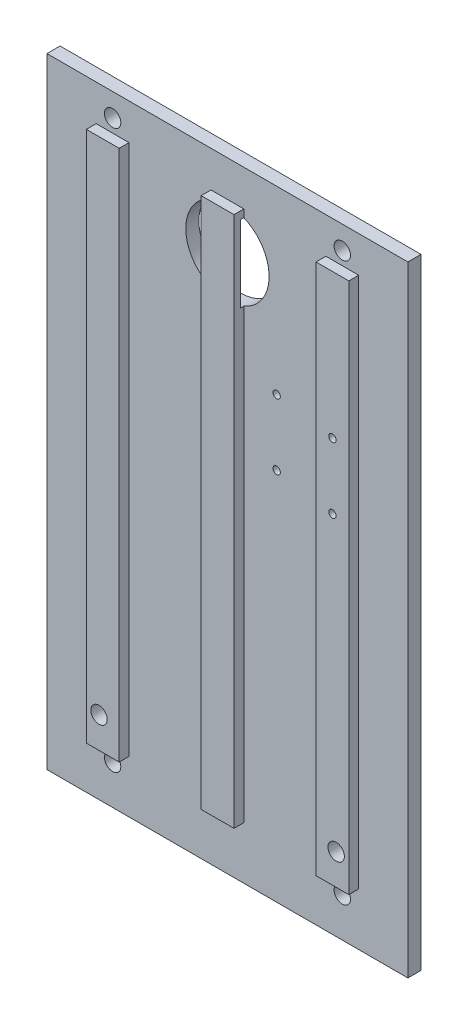
SolidWorks part; units mm, degrees
ref_plane "Front Plane" through (0, 0, 0) normal (0, 0, 1) x (1, 0, 0)
ref_plane "Top Plane" through (0, 0, 0) normal (0, 1, 0) x (1, 0, 0)
ref_plane "Right Plane" through (0, 0, 0) normal (1, 0, 0) x (0, 0, -1)
sketch "Sketch1" plane through (0, 0, 0) normal (0, 0, 1) x (1, 0, 0)
  line L1 (0, 0) -> (110, 0)
  line L2 (0, 0) -> (0, 189)
  line L3 (0, 189) -> (110, 189)
  line L4 (110, 0) -> (110, 189)
extrude "Boss-Extrude1" add sketch "Sketch1" along normal blind 4
sketch "Sketch2" plane through (0, 0, 4) normal (0, 0, 1) x (1, 0, 0)
  line L0 (55, 189) -> (55, 0) construction
  line L1 (110, 189) -> (0, 189) construction
  line L2 (0, 0) -> (110, 0) construction
  line L3 (0, 189) -> (0, 0) construction
  line L4 (110, 0) -> (110, 189) construction
  line L5 (110, 189) -> (0, 189) construction
  circle A1 centre (20, 12) radius 2.5
  circle A2 centre (90, 12) radius 2.5
  circle A3 centre (18.86, 25.4) radius 2.5
  circle A4 centre (91.14, 25.4) radius 2.5
  circle A5 centre (20, 182) radius 2.5
  circle A6 centre (90, 182) radius 2.5
  circle A7 centre (20, 134) radius 1.12 construction
  circle A8 centre (40, 134) radius 1.12 construction
  circle A9 centre (20, 114) radius 1.12 construction
  circle A10 centre (40, 114) radius 1.12 construction
  circle A11 centre (55, 164) radius 12.7
  circle A12 centre (70, 134) radius 1.12
  circle A13 centre (90, 134) radius 1.12
  circle A14 centre (90, 114) radius 1.12
  circle A15 centre (70, 114) radius 1.12
  dimension "D1" = 5
  dimension "D2" = 5
  dimension "D3" = 12
  dimension "D4" = 12
  dimension "D5" = 20
  dimension "D6" = 20
  dimension "D7" = 5
  dimension "D8" = 5
  dimension "D9" = 18.86
  dimension "D10" = 18.86
  dimension "D11" = 25.4
  dimension "D12" = 25.4
  dimension "D13" = 5
  dimension "D14" = 5
  dimension "D15" = 20
  dimension "D16" = 20
  dimension "D17" = 7
  dimension "D18" = 7
  dimension "D19" = 20
  dimension "D20" = 20
  dimension "D21" = 20
  dimension "D22" = 20
  dimension "D23" = 20
  dimension "D24" = 0
  dimension "D25" = 55
  dimension "D26" = 25
sketch "Sketch3" plane through (0, 0, 4) normal (0, 0, 1) x (1, 0, 0)
  line L0 (0, 16) -> (110, 16) construction
  line L1 (0, 189) -> (0, 0) construction
  line L2 (110, 0) -> (110, 189) construction
  line L3 (0, 0) -> (110, 0) construction
  line L4 (0, 178) -> (110, 178) construction
  line L5 (110, 189) -> (0, 189) construction
  line L6 (55, 189) -> (55, 0) construction
  line L7 (50, 178) -> (60, 178)
  line L8 (50, 178) -> (50, 16)
  line L9 (50, 16) -> (60, 16)
  line L10 (60, 178) -> (60, 16)
  line L12 (15, 178) -> (25, 178)
  line L13 (15, 178) -> (15, 16)
  line L14 (15, 16) -> (25, 16)
  line L15 (25, 178) -> (25, 16)
  line L16 (85, 178) -> (95, 178)
  line L17 (85, 178) -> (85, 16)
  line L18 (85, 16) -> (95, 16)
  line L19 (95, 178) -> (95, 16)
  circle A0 centre (20, 182) radius 2.5 construction
  circle A1 centre (90, 182) radius 2.5 construction
  dimension "D1" = 16
  dimension "D2" = 11
  dimension "D3" = 10
  dimension "D4" = 5
  dimension "D5" = 10
  dimension "D6" = 5
  dimension "D7" = 5
  dimension "D8" = 10
extrude "Boss-Extrude2" add sketch "Sketch3" along normal blind 3
extrude "Cut-Extrude1" cut sketch "Sketch2" against normal blind 146 and the other way blind 5 contours A2 | A1 | A3 | A4 | A5 | A6 | A12 | A13 | A14 | A15
sketch "Sketch4" plane through (0, 0, 0) normal (0, 0, -1) x (-1, 0, 0)
  line L0 (-55, 189) -> (-55, 0) construction
  line L1 (-110, 189) -> (0, 189) construction
  line L2 (0, 0) -> (-110, 0) construction
  circle A0 centre (-55, 164) radius 12.7
  dimension "D1" = 25
  dimension "D2" = 25.4
extrude "Cut-Extrude2" cut sketch "Sketch4" against normal blind 5
